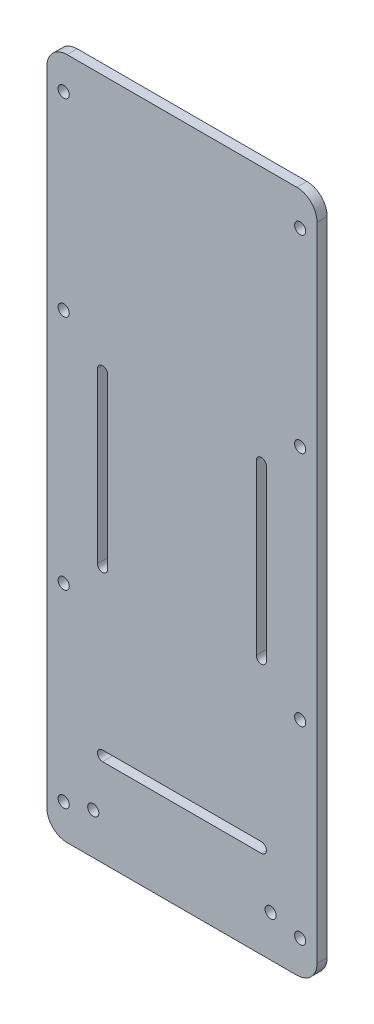
SolidWorks part; units mm, degrees
ref_plane "Спереди" through (0, 0, 0) normal (0, 0, 1) x (1, 0, 0)
ref_plane "Сверху" through (0, 0, 0) normal (0, 1, 0) x (1, 0, 0)
ref_plane "Справа" through (0, 0, 0) normal (1, 0, 0) x (0, 0, -1)
sketch "Эскиз1" plane through (0, 0, 0) normal (0, 0, 1) x (1, 0, 0)
  line L0 (-357.5893, 0) -> (17521.8739, 0) construction
  line L1 (0, -357.5893) -> (0, 17521.8739) construction
  line L3 (-34, 101) -> (34, 101)
  line L4 (-40, 95) -> (-40, -95)
  line L5 (-34, -101) -> (34, -101)
  line L6 (40, 95) -> (40, -95)
  circle A0 centre (-35, 91) radius 1.65
  circle A1 centre (-35, 35) radius 1.65
  arc A2 (-40, -95) -> (-34, -101) centre (-34, -95) ccw
  arc A3 (34, -101) -> (40, -95) centre (34, -95) ccw
  arc A4 (34, 101) -> (40, 95) centre (34, 95) cw
  arc A5 (-40, 95) -> (-34, 101) centre (-34, 95) cw
  circle A6 centre (35, 35) radius 1.65
  circle A7 centre (35, 91) radius 1.65
  circle A8 centre (35, -91) radius 1.65
  circle A9 centre (-35, -91) radius 1.65
  circle A10 centre (-35, -35) radius 1.65
  circle A11 centre (35, -35) radius 1.65
  point P21 (40, -101)
  point P24 (40, 101)
  point P27 (-40, 101)
  dimension "D1" = 3.3
  dimension "D7" = 6
  dimension "D2" = 80
  dimension "D3" = 202
  dimension "D4" = 35
  dimension "D5" = 10
  dimension "D6" = 5
extrude "Бобышка-Вытянуть1" add sketch "Эскиз1" along normal blind 3
sketch "Эскиз2" plane through (0, 0, 3) normal (0, 0, 1) x (1, 0, 0)
  line L0 (-1000, 0) -> (49000, 0) construction
  line L1 (0, -1000) -> (0, 49000) construction
  line L2 (-23.5, 25) -> (-23.5, -25) construction
  line L3 (-20, 70) -> (20, 70) construction
  line L4 (-20, 70) -> (-20, -70) construction
  line L5 (-20, -70) -> (20, -70) construction
  line L6 (20, 70) -> (20, -70) construction
  line L7 (-22, 25) -> (-22, -25)
  line L8 (-25, 25) -> (-25, -25)
  line L9 (23.5, 25) -> (23.5, -25) construction
  line L10 (22, 25) -> (22, -25)
  line L11 (25, 25) -> (25, -25)
  line L12 (-34, -101) -> (34, -101) construction
  line L16 (-23.5, -73.5) -> (23.5, -73.5) construction
  line L17 (-23.5, -75) -> (23.5, -75)
  line L18 (-23.5, -72) -> (23.5, -72)
  arc A0 (-22, 25) -> (-25, 25) centre (-23.5, 25) ccw
  arc A1 (-25, -25) -> (-22, -25) centre (-23.5, -25) ccw
  arc A2 (22, 25) -> (25, 25) centre (23.5, 25) cw
  arc A3 (25, -25) -> (22, -25) centre (23.5, -25) cw
  arc A6 (-23.5, -75) -> (-23.5, -72) centre (-23.5, -73.5) cw
  arc A7 (23.5, -72) -> (23.5, -75) centre (23.5, -73.5) cw
  circle A8 centre (-26.25, -88.75) radius 1.65
  circle A9 centre (26.25, -88.75) radius 1.65
  circle A10 centre (-35, -91) radius 1.65 construction
  point P9 (-23.5, 0)
  point P22 (23.5, 0)
  point P29 (0, 0)
  point P30 (-26.75, -89.1856)
  point P31 (0, 0)
  point P37 (0, -73.5)
  dimension "D4" = 3
  dimension "D1" = 40
  dimension "D2" = 140
  dimension "D3" = 2
  dimension "D5" = 50
  dimension "D6" = 27.5
  dimension "D7" = 52.5
  dimension "D8" = 12.25
extrude "Вырез-Вытянуть1" cut sketch "Эскиз2" against normal through all
